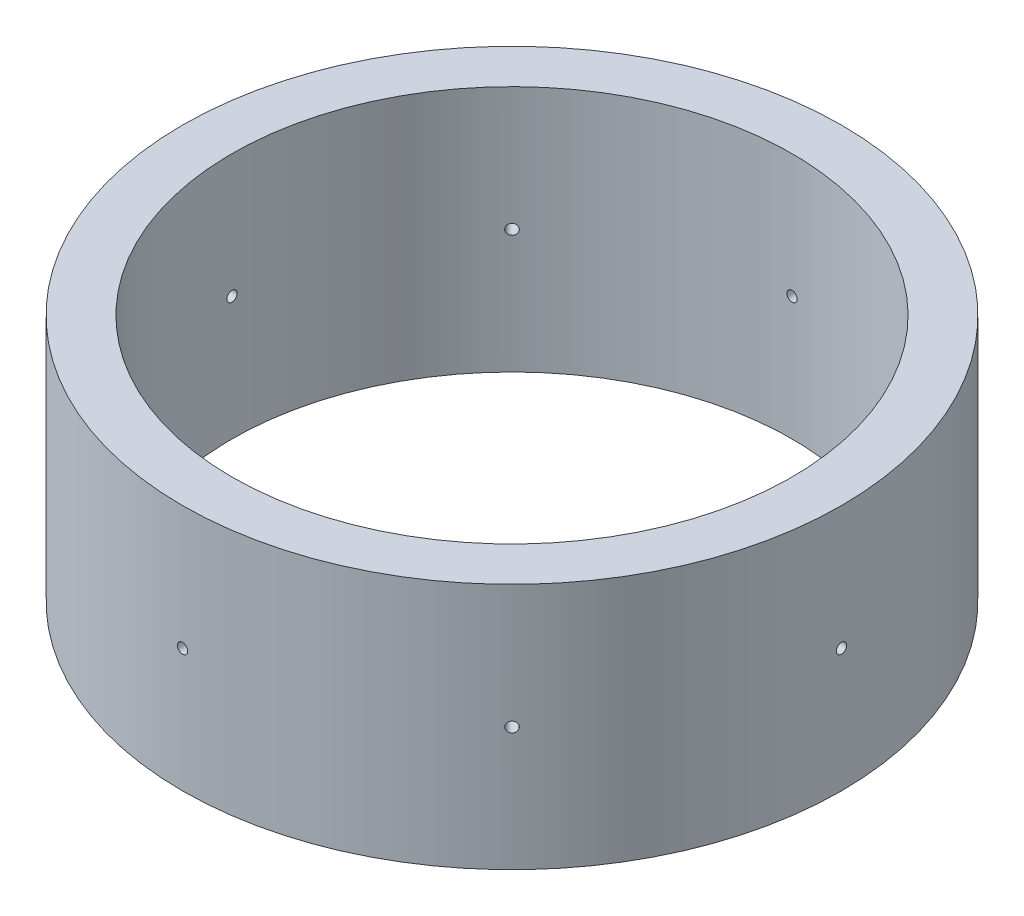
SolidWorks part; units mm, degrees
material "Thornel Mat VMA"
ref_plane "Front Plane" through (0, 0, 0) normal (0, 0, 1) x (1, 0, 0)
ref_plane "Top Plane" through (0, 0, 0) normal (0, 1, 0) x (1, 0, 0)
ref_plane "Right Plane" through (0, 0, 0) normal (1, 0, 0) x (0, 0, -1)
sketch "Sketch1" plane through (0, 0, 0) normal (0, 1, 0) x (1, 0, 0)
  circle A0 centre (0, 0) radius 101.6
  circle A1 centre (0, 0) radius 86.36
  dimension "D1" = 203.2
  dimension "D2" = 172.72
extrude "Boss-Extrude1" add sketch "Sketch1" along normal blind 76.2
ref_plane "Plane1" through (0, 0, 101.6) normal (0, 0, 1) x (1, 0, 0)
sketch "Sketch2" plane through (0, 0, 101.6) normal (0, 0, 1) x (1, 0, 0)
  circle A0 centre (0, 38.1) radius 1.5875
  dimension "D1" = 3.175
  dimension "D2" = 38.1
extrude "Cut-Extrude1" cut sketch "Sketch2" against normal up to next
pattern_circular "CirPattern1" count 8 over 360 about axis through (0, 76.2, 0) along (0, -1, 0) of "Cut-Extrude1"
